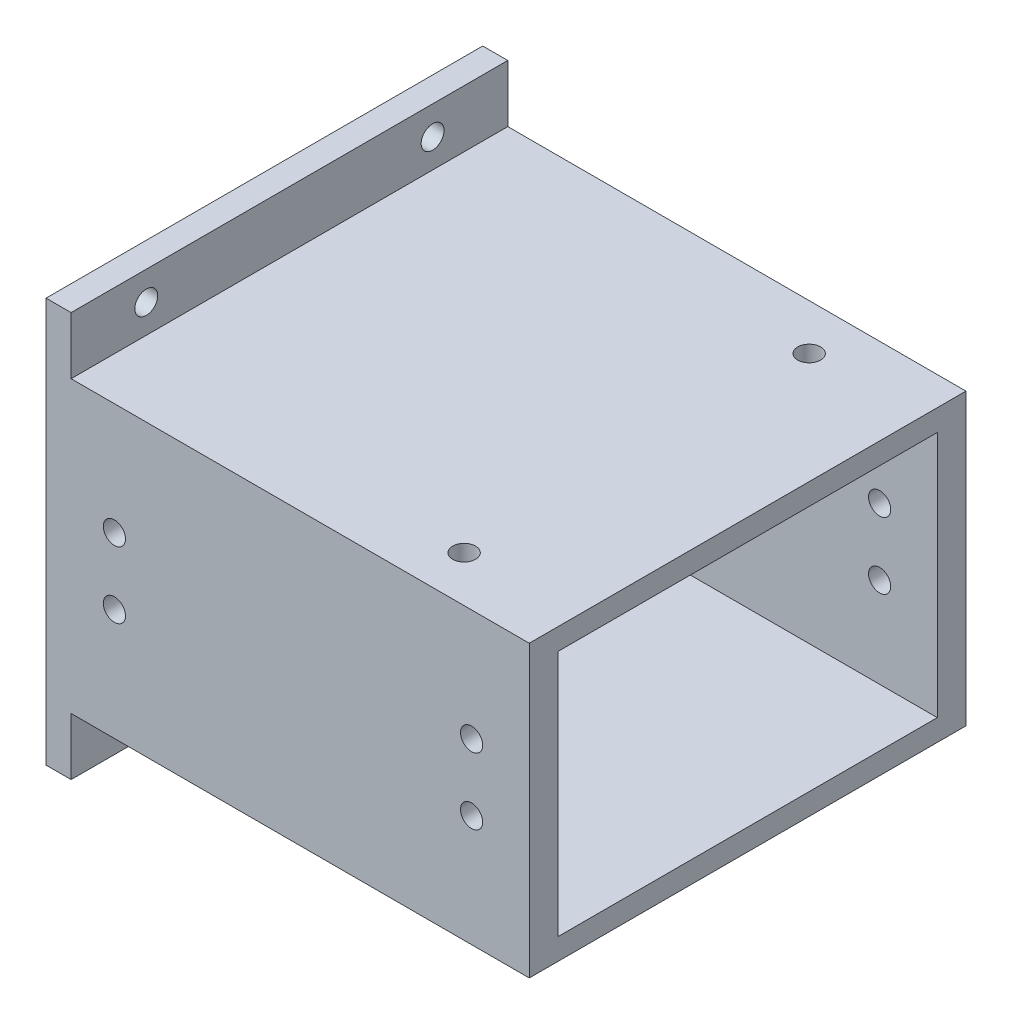
SolidWorks part; units mm, degrees
ref_plane "정면" through (0, 0, 0) normal (0, 0, 1) x (1, 0, 0)
ref_plane "윗면" through (0, 0, 0) normal (0, 1, 0) x (1, 0, 0)
ref_plane "우측면" through (0, 0, 0) normal (1, 0, 0) x (0, 0, -1)
sketch "Sketch1" plane through (0, 0, 0) normal (0, 1, 0) x (1, 0, 0)
  line L0 (-75.5, 30.5) -> (75.5, 30.5)
  line L1 (-71.5, 26.5) -> (71.5, 26.5)
  line L2 (-71.5, 26.5) -> (-71.5, -26.5)
  line L3 (-71.5, -26.5) -> (71.5, -26.5)
  line L4 (71.5, 26.5) -> (71.5, -26.5)
  line L5 (-71.5, 26.5) -> (71.5, -26.5) construction
  line L6 (-71.5, -26.5) -> (71.5, 26.5) construction
  line L7 (75.5, 30.5) -> (75.5, -30.5)
  line L8 (-75.5, -30.5) -> (75.5, -30.5)
  line L9 (-75.5, 30.5) -> (-75.5, -30.5)
  point P0 (0, 0)
  dimension "D1" = 143
  dimension "D2" = 53
  dimension "D3" = 4
extrude "Boss-Extrude1" add sketch "Sketch1" along normal mid plane 40.5
sketch "Sketch2" plane through (0, -20.25, 0) normal (0, -1, 0) x (1, 0, 0)
  line L1 (-71.5, 26.5) -> (71.5, 26.5)
  line L2 (-71.5, 26.5) -> (-71.5, -26.5)
  line L3 (-71.5, -26.5) -> (71.5, -26.5)
  line L4 (71.5, 26.5) -> (71.5, -26.5)
extrude "Boss-Extrude2" add sketch "Sketch2" against normal blind 3
sketch "Sketch7" plane through (75.5, 0, 0) normal (1, 0, 0) x (0, 0, -1)
  line L0 (-30.5, 20.25) -> (30.5, 20.25) construction
  line L1 (-26.5, 20.25) -> (26.5, 20.25)
  line L2 (-26.5, 20.25) -> (-26.5, -17.25)
  line L3 (-26.5, -17.25) -> (26.5, -17.25)
  line L4 (26.5, 20.25) -> (26.5, -17.25)
  line L6 (26.5, -17.25) -> (-26.5, -17.25) construction
  line L7 (26.5, -17.25) -> (-26.5, -17.25) construction
  point P7 (0, 20.25)
  dimension "D2" = 53
extrude "Cut-Extrude3" cut sketch "Sketch7" against normal blind 4 contours L4 L3 L2 L1
sketch "Sketch9" plane through (0, 20.25, 0) normal (0, 1, 0) x (1, 0, 0)
  line L0 (-71.5, -26.5) -> (-71.5, 26.5) construction
  line L1 (-71.5, 26.5) -> (75.5, 26.5) construction
  line L2 (75.5, -26.5) -> (-71.5, -26.5) construction
  line L3 (75.5, -26.5) -> (75.5, 26.5) construction
  line L4 (-71.5, -26.5) -> (-71.5, 26.5)
  line L5 (-71.5, 26.5) -> (75.5, 26.5)
  line L6 (75.5, -26.5) -> (-71.5, -26.5)
  line L7 (75.5, -26.5) -> (75.5, 26.5)
extrude "Boss-Extrude3" add sketch "Sketch9" against normal blind 3
sketch "Sketch10" plane through (0, 20.25, 0) normal (0, 1, 0) x (1, 0, 0)
  line L0 (-75.5, 0) -> (75.5, 0) construction
  line L1 (-75.5, 30.5) -> (-75.5, -30.5) construction
  line L2 (75.5, -30.5) -> (75.5, 30.5) construction
  line L3 (60, 0) -> (60, 24.1) construction
  line L4 (-6.04, 0) -> (-6.04, 21) construction
  circle A0 centre (60, 24.1) radius 1.6
  circle A1 centre (60, -24.1) radius 1.6
  circle A2 centre (-6.04, 21) radius 1.6
  circle A3 centre (-6.04, -21) radius 1.6
  dimension "D2" = 3.2
  dimension "D5" = 3.2
  dimension "D1" = 24.1
  dimension "D3" = 15.5
  dimension "D4" = 21
  dimension "D6" = 66.04
extrude "Cut-Extrude4" cut sketch "Sketch10" against normal up to next
sketch "Sketch12" plane through (0, 0, 30.5) normal (0, 0, 1) x (1, 0, 0)
  line L0 (75.5, 0) -> (-31.9096, 0) construction
  line L1 (75.5, 20.25) -> (75.5, -20.25) construction
  line L2 (67.4452, 4.65) -> (67.4452, -4.65) construction
  line L3 (67.4452, 4.65) -> (17.5452, 4.65) construction
  circle A0 centre (67.4452, 4.65) radius 1.55
  circle A1 centre (67.4452, -4.65) radius 1.55
  circle A2 centre (17.5452, 4.65) radius 1.55
  circle A3 centre (17.5452, -4.65) radius 1.55
  point P7 (67.4452, 0)
  dimension "D2" = 49.9
  dimension "D3" = 3.1
  dimension "D4" = 3.1
  dimension "D1" = 9.3
extrude "Cut-Extrude6" cut sketch "Sketch12" against normal through all
ref_plane "Plane1" through (0, 0, 17) normal (0, 0, 1) x (1, 0, 0)
sketch "Sketch13" plane through (0, 0, 17) normal (0, 0, 1) x (1, 0, 0)
  line L0 (-75.5, 20.25) -> (-75.5, -20.25) construction
  line L1 (-72.87, 20.25) -> (-65.87, 20.25)
  line L2 (-72.87, 20.25) -> (-72.87, 39.61)
  line L3 (-72.87, 39.61) -> (-65.87, 39.61)
  line L4 (-65.87, 20.25) -> (-65.87, 39.61)
  line L6 (-75.5, 20.25) -> (75.5, 20.25) construction
  dimension "D1" = 2.63
  dimension "D2" = 7
  dimension "D3" = 19.36
extrude "Boss-Extrude4" add sketch "Sketch13" along normal blind 2
sketch "Sketch16" plane through (0, 0, 19) normal (0, 0, 1) x (1, 0, 0)
  line L0 (-69.2622, 20.25) -> (-69.2622, 39.61) construction
  line L3 (-75.5, 20.25) -> (75.5, 20.25) construction
  line L4 (-72.87, 20.25) -> (-65.87, 20.25) construction
  line L5 (-65.87, 39.61) -> (-72.87, 39.61) construction
  circle A0 centre (-69.2622, 24.85) radius 1.6
  circle A1 centre (-69.2622, 34.85) radius 1.6
  point P8 (-69.2622, 23.25)
  point P11 (-69.2622, 34.85)
  dimension "D1" = 3.2
  dimension "D4" = 3.2
  dimension "D2" = 3
  dimension "D3" = 10
extrude "Cut-Extrude7" cut sketch "Sketch16" against normal blind 10
ref_plane "Plane3" through (-65.87, 0, 0) normal (1, 0, 0) x (0, 0, -1)
ref_plane "Plane4" through (-44.87, 0, 0) normal (1, 0, 0) x (0, 0, -1)
mirror "Mirror1" about plane through (-44.87, 0, 0) normal (1, 0, 0) of "Cut-Extrude7", "Boss-Extrude4"
sketch "Sketch17" plane through (0, 0, -30.5) normal (0, 0, -1) x (-1, 0, 0)
  line L0 (-75.5, 20.25) -> (75.5, 20.25) construction
  line L1 (58.81, 20.25) -> (51.81, 20.25)
  line L2 (58.81, 20.25) -> (58.81, 35.25)
  line L3 (58.81, 35.25) -> (51.81, 35.25)
  line L4 (51.81, 20.25) -> (51.81, 35.25)
  line L5 (55.31, 20.25) -> (55.31, 35.25) construction
  line L6 (75.5, 20.25) -> (75.5, -20.25) construction
  circle A0 centre (55.31, 30.15) radius 2
  point P8 (55.31, 30.15)
  dimension "D2" = 4
  dimension "D1" = 9.9
  dimension "D3" = 20.19
  dimension "D4" = 7
  dimension "D5" = 15
extrude "Boss-Extrude5" add sketch "Sketch17" against normal blind 3
sketch "Sketch18" plane through (0, -20.25, 0) normal (0, -1, 0) x (1, 0, 0)
  line L0 (-56.5, 30.5) -> (-56.5, -30.5) construction
  line L1 (-75.5, 30.5) -> (75.5, 30.5) construction
  line L2 (75.5, -30.5) -> (-75.5, -30.5) construction
  line L3 (-75.5, 0) -> (75.5, 0) construction
  line L4 (-75.5, -30.5) -> (-75.5, 30.5) construction
  line L5 (75.5, 30.5) -> (75.5, -30.5) construction
  circle A0 centre (-56.5, 20) radius 1.6
  circle A1 centre (-56.5, -20) radius 1.6
  point P12 (-56.5, 20)
  point P13 (-56.5, -20)
  dimension "D3" = 19
  dimension "D1" = 20
  dimension "D2" = 20
extrude "Cut-Extrude8" cut sketch "Sketch18" against normal blind 10
sketch "Sketch19" plane through (0, 0, 30.5) normal (0, 0, 1) x (1, 0, 0)
  line L1 (-68.5, -17.25) -> (-43.5, -17.25)
  line L2 (-68.5, -17.25) -> (-68.5, -5.25)
  line L3 (-68.5, -5.25) -> (-43.5, -5.25)
  line L4 (-43.5, -17.25) -> (-43.5, -5.25)
  line L5 (-75.5, 20.25) -> (-75.5, -20.25) construction
  dimension "D1" = 7
  dimension "D2" = 25
  dimension "D3" = 12
extrude "Cut-Extrude9" cut sketch "Sketch19" against normal through all
sketch "Sketch20" plane through (0, 20.25, 0) normal (0, 1, 0) x (1, 0, 0)
  line L0 (-75.5, -30.5) -> (75.5, -30.5) construction
  line L1 (4.5, -30.5) -> (11.5, -30.5)
  line L2 (4.5, -30.5) -> (4.5, 30.5)
  line L3 (4.5, 30.5) -> (11.5, 30.5)
  line L4 (11.5, -30.5) -> (11.5, 30.5)
  line L5 (75.5, 30.5) -> (-51.81, 30.5) construction
  line L6 (-75.5, 30.5) -> (-75.5, -30.5) construction
  dimension "D1" = 7
  dimension "D2" = 80
extrude "Boss-Extrude6" add sketch "Sketch20" along normal blind 8
sketch "Sketch21" plane through (4.5, 0, 0) normal (-1, 0, 0) x (0, 0, 1)
  line L0 (30.5, 24.25) -> (-30.5, 24.25) construction
  line L1 (30.5, 28.25) -> (30.5, 20.25) construction
  line L2 (-30.5, 20.25) -> (-30.5, 35.25) construction
  line L3 (0, 28.25) -> (0, 20.25) construction
  line L4 (-30.5, 28.25) -> (30.5, 28.25) construction
  line L5 (-30.5, 20.25) -> (30.5, 20.25) construction
  circle A0 centre (-20, 24.25) radius 1.6
  circle A1 centre (20, 24.25) radius 1.6
  dimension "D1" = 20
extrude "Cut-Extrude10" cut sketch "Sketch21" against normal up to next
mirror "Mirror2" about plane through (0, 0, 0) normal (0, 1, 0) of "Cut-Extrude10", "Boss-Extrude6"
sketch "Sketch22" plane through (0, 0, 0) normal (0, 1, 0) x (1, 0, 0)
  line L1 (8, 36.9778) -> (-82.9035, 36.9778)
  line L2 (8, 36.9778) -> (8, -36.9777)
  line L3 (8, -36.9777) -> (-82.9035, -36.9777)
  line L4 (-82.9035, 36.9778) -> (-82.9035, -36.9777)
  line L5 (-75.5, 30.5) -> (-75.5, -30.5) construction
  dimension "D1" = 83.5
extrude "Cut-Extrude11" cut sketch "Sketch22" against normal through all both and the other way through all
